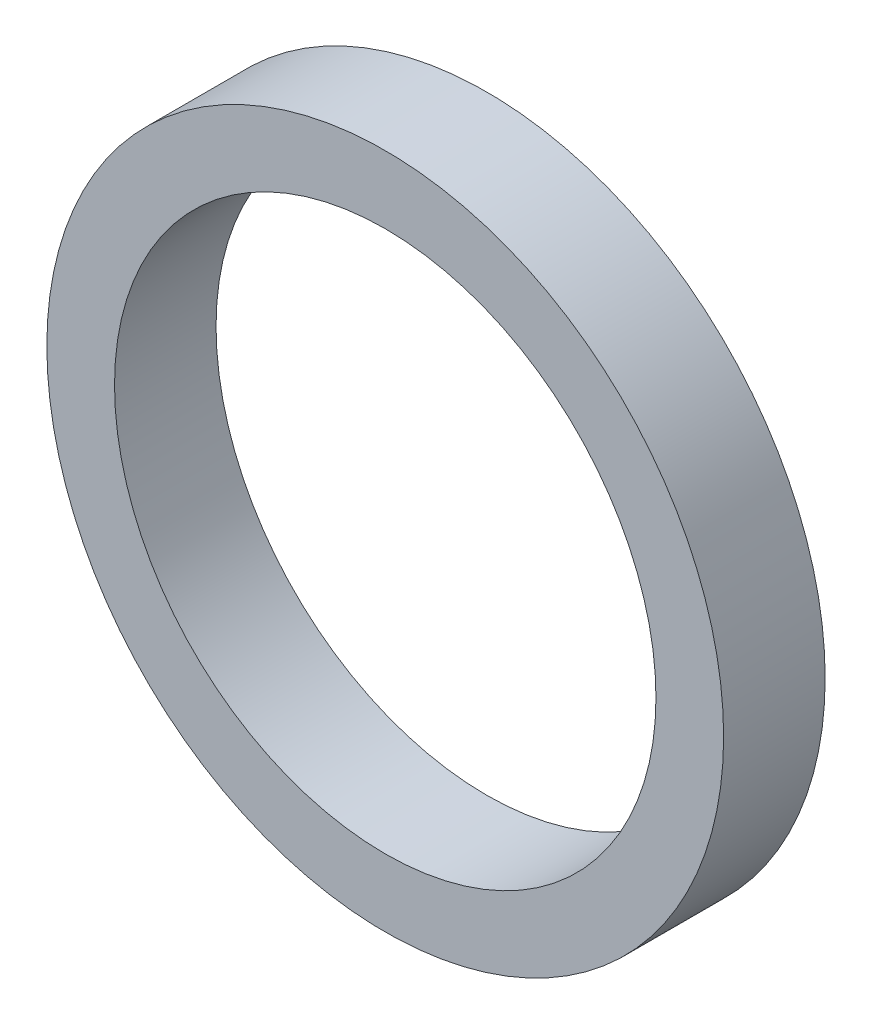
SolidWorks part; units mm, degrees
ref_plane "Front Plane" through (0, 0, 0) normal (0, 0, 1) x (1, 0, 0)
ref_plane "Top Plane" through (0, 0, 0) normal (0, 1, 0) x (1, 0, 0)
ref_plane "Right Plane" through (0, 0, 0) normal (1, 0, 0) x (0, 0, -1)
sketch "Sketch1" plane through (0, 0, 0) normal (0, 0, 1) x (1, 0, 0)
  circle A0 centre (0, 0) radius 8
  circle A1 centre (0, 0) radius 10
extrude "Boss-Extrude1" add sketch "Sketch1" along normal blind 3
